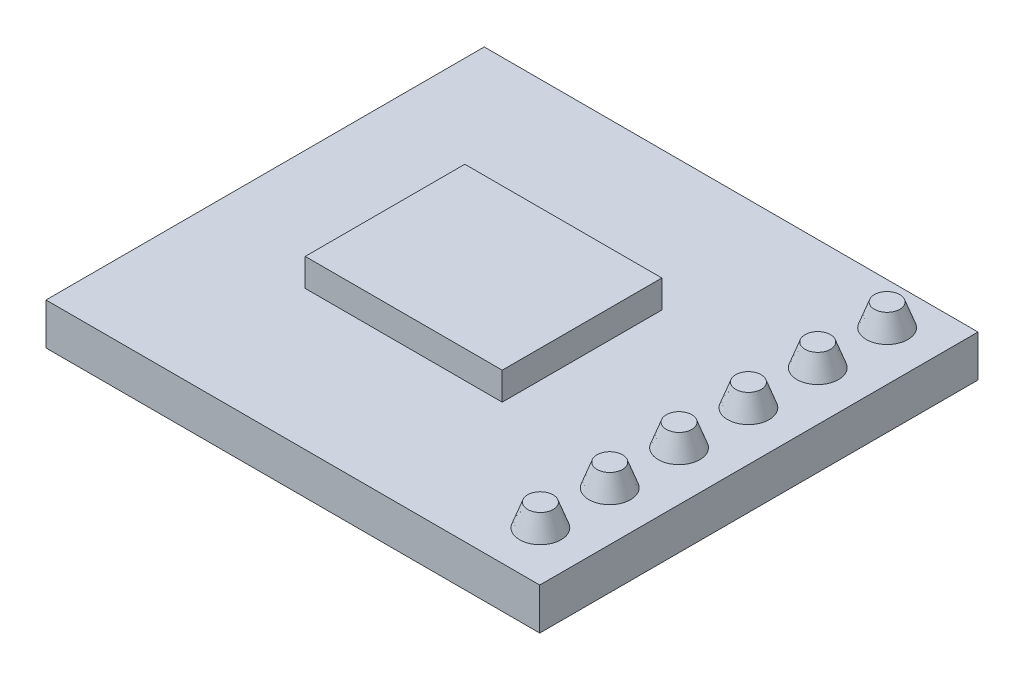
SolidWorks part; units mm, degrees
ref_plane "Front Plane" through (0, 0, 0) normal (0, 0, 1) x (1, 0, 0)
ref_plane "Top Plane" through (0, 0, 0) normal (0, 1, 0) x (1, 0, 0)
ref_plane "Right Plane" through (0, 0, 0) normal (1, 0, 0) x (0, 0, -1)
sketch "Sketch1" plane through (0, 0, 0) normal (0, 1, 0) x (1, 0, 0)
  line L1 (-8.9, 7.9) -> (8.9, 7.9)
  line L2 (-8.9, 7.9) -> (-8.9, -7.9)
  line L3 (-8.9, -7.9) -> (8.9, -7.9)
  line L4 (8.9, 7.9) -> (8.9, -7.9)
  line L5 (-8.9, 7.9) -> (8.9, -7.9) construction
  line L6 (-8.9, -7.9) -> (8.9, 7.9) construction
  point P0 (0, 0)
  dimension "D1" = 15.8
  dimension "D2" = 17.8
extrude "Boss-Extrude1" add sketch "Sketch1" along normal blind 1.5
sketch "Sketch2" plane through (0, 1.5, 0) normal (0, 1, 0) x (1, 0, 0)
  line L1 (-4.5879, 2.8876) -> (2.5153, 2.8876)
  line L2 (-4.5879, 2.8876) -> (-4.5879, -2.8674)
  line L3 (-4.5879, -2.8674) -> (2.5153, -2.8674)
  line L4 (2.5153, 2.8876) -> (2.5153, -2.8674)
extrude "Boss-Extrude2" add sketch "Sketch2" along normal blind 1
sketch "Sketch3" plane through (0, 1.5, 0) normal (0, 1, 0) x (1, 0, 0)
  line L0 (8.9, 7.9) -> (-8.9, 7.9) construction
  circle A0 centre (7.1233, 6.4) radius 0.75
  circle A1 centre (7.1233, 3.9) radius 0.75
  circle A2 centre (7.1233, 1.4) radius 0.75
  circle A3 centre (7.1233, -1.1) radius 0.75
  circle A4 centre (7.1233, -3.6) radius 0.75
  circle A5 centre (7.1233, -6.1) radius 0.75
  dimension "D1" = 1.5
  dimension "D2" = 1.5
  dimension "D3" = 6
extrude "Boss-Extrude3" add sketch "Sketch3" along normal blind 0.8 draft 20
